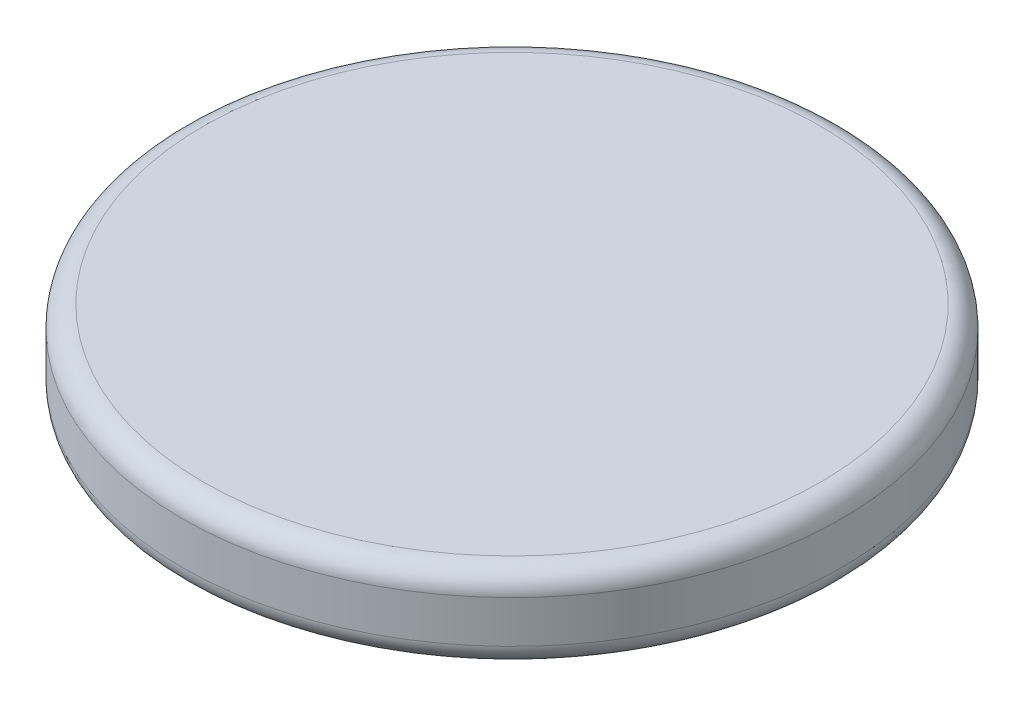
SolidWorks part; units mm, degrees
ref_plane "Front Plane" through (0, 0, 0) normal (0, 0, 1) x (1, 0, 0)
ref_plane "Top Plane" through (0, 0, 0) normal (0, 1, 0) x (1, 0, 0)
ref_plane "Right Plane" through (0, 0, 0) normal (1, 0, 0) x (0, 0, -1)
sketch "Sketch1" plane through (0, 0, 0) normal (0, 1, 0) x (1, 0, 0)
  circle A0 centre (0, 0) radius 49.53
  dimension "D1" = 99.06
extrude "Boss-Extrude1" add sketch "Sketch1" along normal blind 12.7 contours A0
fillet "Fillet1" radius 3.175 2 edges at (0, 0, 49.53) (0, 12.7, 49.53)
